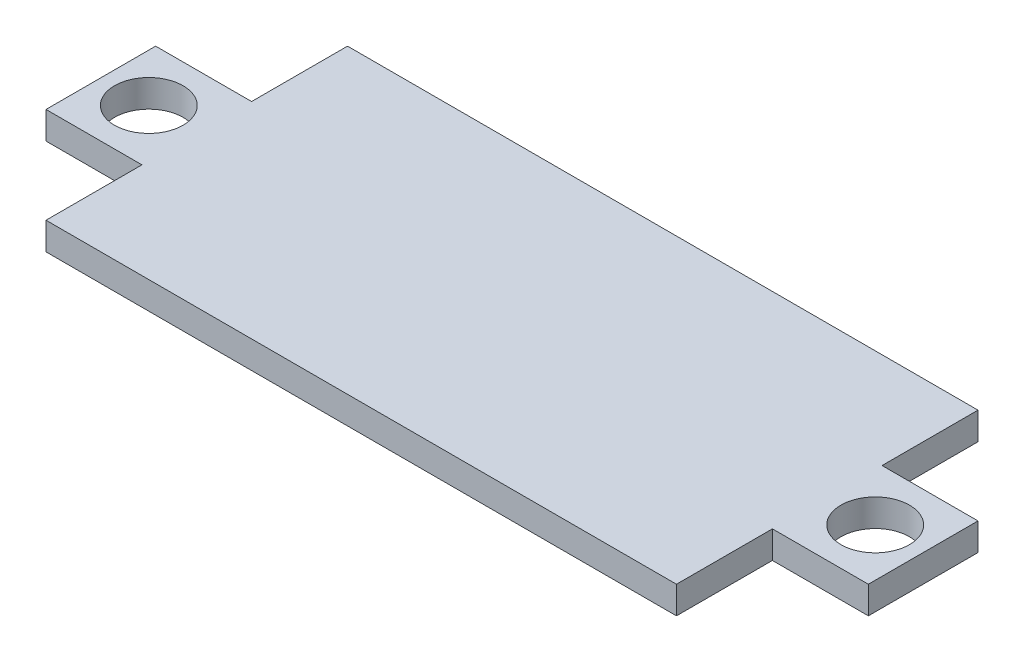
SolidWorks part; units mm, degrees
ref_plane "前视基准面" through (0, 0, 0) normal (0, 0, 1) x (1, 0, 0)
ref_plane "上视基准面" through (0, 0, 0) normal (0, 1, 0) x (1, 0, 0)
ref_plane "右视基准面" through (0, 0, 0) normal (1, 0, 0) x (0, 0, -1)
sketch "草图1" plane through (0, 0, 0) normal (0, 1, 0) x (1, 0, 0)
  line L1 (-23.4605, 13.7299) -> (-0.4605, 13.7299)
  line L2 (-26.9605, 10.2299) -> (-26.9605, 6.2299)
  line L3 (-23.4605, 2.7299) -> (-0.4605, 2.7299)
  line L4 (3.0395, 10.2299) -> (3.0395, 6.2299)
  line L7 (-26.9605, 10.2299) -> (-23.4605, 10.2299)
  line L8 (-23.4605, 13.7299) -> (-23.4605, 10.2299)
  line L11 (-26.9605, 6.2299) -> (-23.4605, 6.2299)
  line L12 (-23.4605, 2.7299) -> (-23.4605, 6.2299)
  line L15 (3.0395, 10.2299) -> (-0.4605, 10.2299)
  line L16 (-0.4605, 13.7299) -> (-0.4605, 10.2299)
  line L19 (3.0395, 6.2299) -> (-0.4605, 6.2299)
  line L20 (-0.4605, 2.7299) -> (-0.4605, 6.2299)
  circle A0 centre (1.2895, 8.2299) radius 1.25
  circle A1 centre (-25.2105, 8.2299) radius 1.25
  point P22 (3.0395, 8.435)
  dimension "D1" = 3.5
  dimension "D5" = 2.5
  dimension "D6" = 2.5
  dimension "D8" = 1.75
  dimension "D9" = 1.75
  dimension "D10" = 2
  dimension "D2" = 3.5
  dimension "D3" = 3.5
  dimension "D4" = 3.5
  dimension "D7" = 2
extrude "凸台-拉伸1" add sketch "草图1" along normal blind 1
